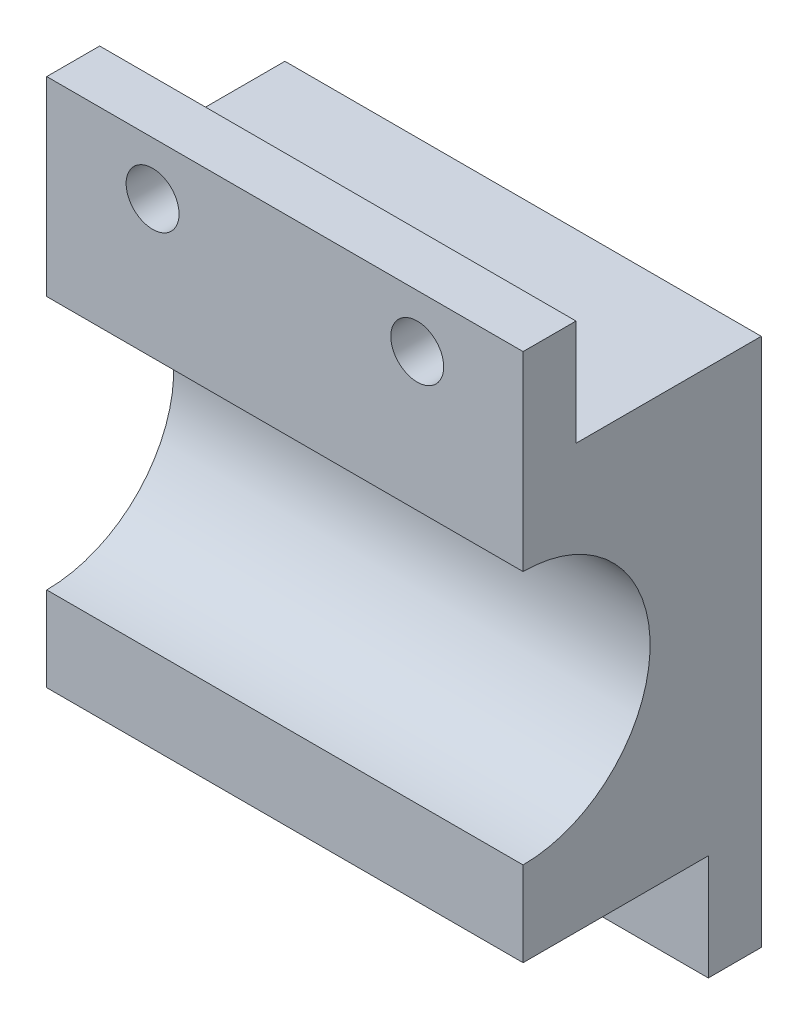
SolidWorks part; units mm, degrees
material "不锈钢 (铁素体)"
ref_plane "前视" through (0, 0, 0) normal (0, 0, 1) x (1, 0, 0)
ref_plane "上视" through (0, 0, 0) normal (0, 1, 0) x (1, 0, 0)
ref_plane "右视" through (0, 0, 0) normal (1, 0, 0) x (0, 0, -1)
sketch "草图1" plane through (0, 0, 0) normal (1, 0, 0) x (0, 0, -1)
  line L0 (0, 0) -> (5, 0)
  line L1 (5, 0) -> (5, -10)
  line L2 (5, -10) -> (22.5, -10)
  line L3 (22.5, -10) -> (22.5, -60)
  line L4 (22.5, -60) -> (17.5, -60)
  line L5 (17.5, -60) -> (17.5, -50)
  line L6 (17.5, -50) -> (0, -50)
  line L7 (0, -50) -> (0, -42)
  line L8 (0, -18) -> (0, 0)
  arc A0 (0, -42) -> (0, -18) centre (0, -30) ccw
  dimension "D1" = 12
  dimension "D2" = 10
  dimension "D3" = 5
  dimension "D4" = 22.5
  dimension "D5" = 40
  dimension "D6" = 20
  dimension "D7" = 5
  dimension "D8" = 10
extrude "凸台-拉伸1" add sketch "草图1" along normal blind 45
sketch "草图2" plane through (0, 0, -22.5) normal (0, 0, -1) x (-1, 0, 0)
  line L0 (-22.5, 13.1509) -> (-22.5, -69.4785) construction
  line L1 (0, -10) -> (0, 0) construction
  line L2 (-45, 0) -> (0, 0) construction
  line L3 (-45, -60) -> (0, -60) construction
  line L4 (-45, -60) -> (-45, -10) construction
  line L5 (0, -60) -> (0, -10) construction
  circle A0 centre (-35, -55) radius 2.5
  circle A1 centre (-10, -5) radius 2.5
  circle A2 centre (-10, -55) radius 2.5
  circle A3 centre (-35, -5) radius 2.5
  dimension "D1" = 5
  dimension "D2" = 10
  dimension "D3" = 5
  dimension "D4" = 5
extrude "切除-拉伸1" cut sketch "草图2" against normal through all
